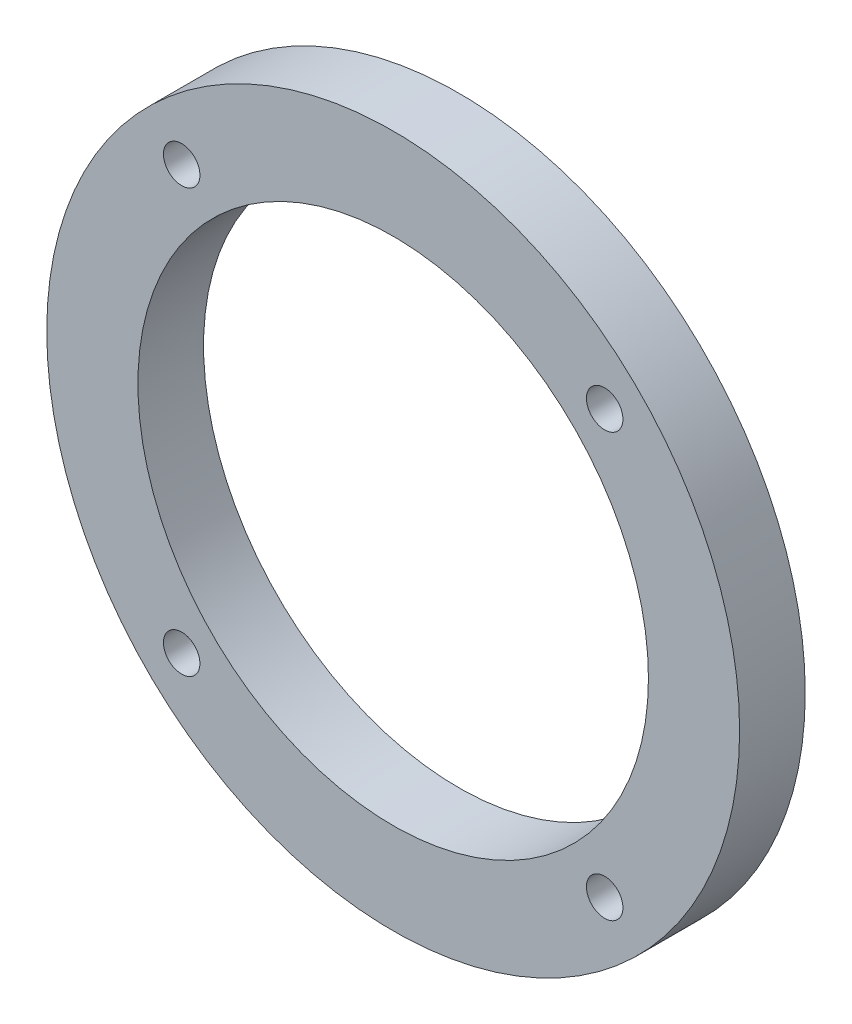
SolidWorks part; units mm, degrees
ref_plane "前视基准面" through (0, 0, 0) normal (0, 0, 1) x (1, 0, 0)
ref_plane "上视基准面" through (0, 0, 0) normal (0, 1, 0) x (1, 0, 0)
ref_plane "右视基准面" through (0, 0, 0) normal (1, 0, 0) x (0, 0, -1)
sketch "草图1" plane through (0, 0, 0) normal (0, 0, 1) x (1, 0, 0)
  circle A0 centre (0, 0) radius 47.5
  circle A1 centre (0, 0) radius 35
  dimension "D1" = 95
  dimension "D2" = 70
extrude "凸台-拉伸1" add sketch "草图1" along normal blind 9
sketch "草图2" plane through (0, 0, 9) normal (0, 0, 1) x (1, 0, 0)
  line L1 (-29, 29) -> (29, 29) construction
  line L2 (-29, 29) -> (-29, -29) construction
  line L3 (-29, -29) -> (29, -29) construction
  line L4 (29, 29) -> (29, -29) construction
  line L5 (-29, 29) -> (29, -29) construction
  line L6 (-29, -29) -> (29, 29) construction
  circle A5 centre (29, 29) radius 2.5
  circle A6 centre (29, -29) radius 2.5
  circle A7 centre (-29, -29) radius 2.5
  circle A8 centre (-29, 29) radius 2.5
  circle A9 centre (0, 0) radius 41.0122 construction
  point P0 (0, 0)
  dimension "D1" = 58
  dimension "D3" = 5
extrude "切除-拉伸1" cut sketch "草图2" against normal blind 10
sketch "草图3" plane through (0, 0, 0) normal (0, 0, -1) x (-1, 0, 0)
  circle A0 centre (0, 0) radius 35 construction
  circle A1 centre (29, 29) radius 2.5 construction
  circle A2 centre (-29, -29) radius 2.5 construction
  circle A3 centre (29, -29) radius 2.5 construction
  circle A4 centre (-29, 29) radius 2.5 construction
  circle A5 centre (0, 0) radius 35
  circle A6 centre (29, 29) radius 2.5
  circle A7 centre (-29, -29) radius 2.5
  circle A8 centre (29, -29) radius 2.5
  circle A9 centre (-29, 29) radius 2.5
